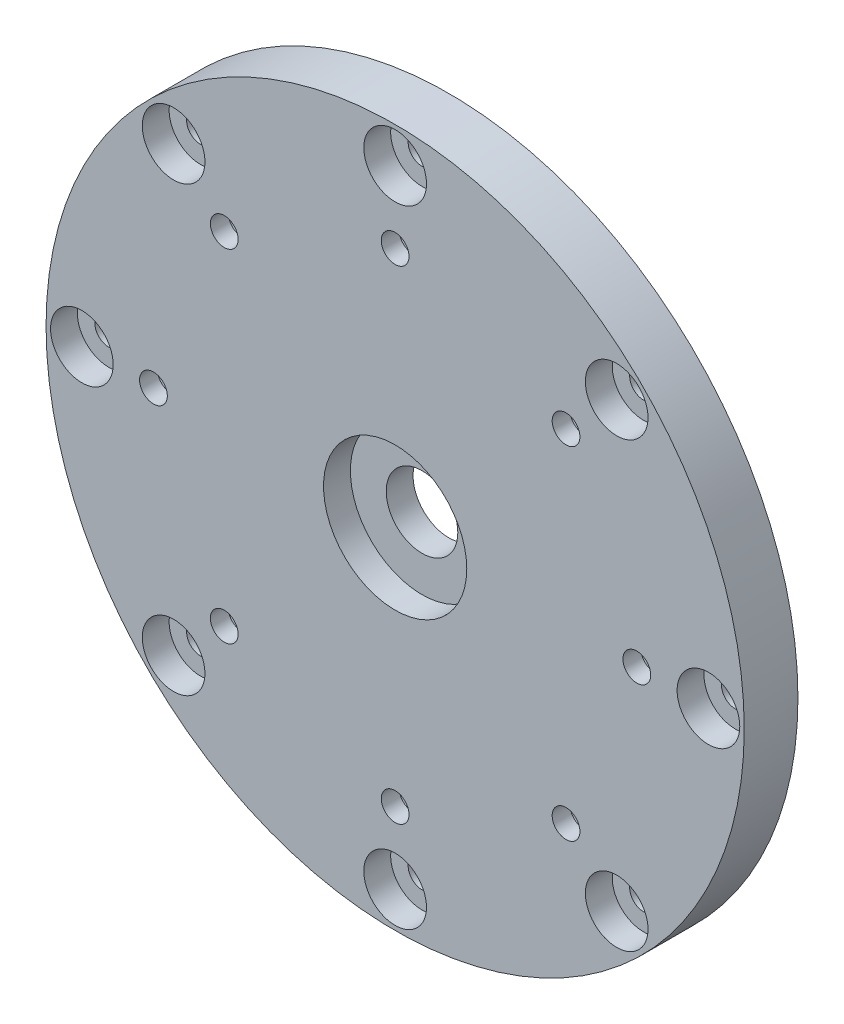
SolidWorks part; units mm, degrees
ref_plane "Front Plane" through (0, 0, 0) normal (0, 0, 1) x (1, 0, 0)
ref_plane "Top Plane" through (0, 0, 0) normal (0, 1, 0) x (1, 0, 0)
ref_plane "Right Plane" through (0, 0, 0) normal (1, 0, 0) x (0, 0, -1)
sketch "Sketch1" plane through (0, 0, 0) normal (0, 0, 1) x (1, 0, 0)
  line L0 (0, 0) -> (-27, 0) construction
  line L1 (0, 0) -> (-35, 0) construction
  circle A1 centre (0, 0) radius 39
  circle A2 centre (-27, 0) radius 1.55
  circle A3 centre (-19.0919, 19.0919) radius 1.55
  circle A4 centre (0, 27) radius 1.55
  circle A5 centre (19.0919, 19.0919) radius 1.55
  circle A6 centre (27, 0) radius 1.55
  circle A7 centre (19.0919, -19.0919) radius 1.55
  circle A8 centre (0, -27) radius 1.55
  circle A9 centre (-19.0919, -19.0919) radius 1.55
  circle A10 centre (0, 0) radius 4
  circle A11 centre (-35, 0) radius 1.55
  circle A12 centre (-24.7487, 24.7487) radius 1.55
  circle A13 centre (0, 35) radius 1.55
  circle A14 centre (24.7487, 24.7487) radius 1.55
  circle A15 centre (35, 0) radius 1.55
  circle A16 centre (24.7487, -24.7487) radius 1.55
  circle A17 centre (0, -35) radius 1.55
  circle A18 centre (-24.7487, -24.7487) radius 1.55
  point P21 (0, 0)
  point P39 (0, 0)
  dimension "D1" = 8
  dimension "D2" = 8
extrude "Boss-Extrude2" add sketch "Sketch1" along normal blind 6
sketch "Sketch2" plane through (0, 0, 6) normal (0, 0, 1) x (1, 0, 0)
  circle A0 centre (0, 0) radius 8
extrude "Cut-Extrude1" cut sketch "Sketch2" against normal blind 3
sketch "Sketch3" plane through (0, 0, 0) normal (0, 0, -1) x (-1, 0, 0)
  circle A0 centre (0, 27) radius 3.5
  circle A1 centre (19.0919, 19.0919) radius 3.5
  circle A2 centre (27, 0) radius 3.5
  circle A3 centre (19.0919, -19.0919) radius 3.5
  circle A4 centre (0, -27) radius 3.5
  circle A5 centre (-19.0919, -19.0919) radius 3.5
  circle A6 centre (-27, 0) radius 3.5
  circle A7 centre (-19.0919, 19.0919) radius 3.5
  point P19 (0, 0)
  point P37 (0, 0)
  dimension "D1" = 8
extrude "Cut-Extrude2" cut sketch "Sketch3" against normal blind 4
sketch "Sketch4" plane through (0, 0, 6) normal (0, 0, 1) x (1, 0, 0)
  circle A0 centre (-35, 0) radius 3.5
  circle A1 centre (-24.7487, 24.7487) radius 3.5
  circle A2 centre (0, 35) radius 3.5
  circle A3 centre (24.7487, 24.7487) radius 3.5
  circle A4 centre (35, 0) radius 3.5
  circle A5 centre (24.7487, -24.7487) radius 3.5
  circle A6 centre (0, -35) radius 3.5
  circle A7 centre (-24.7487, -24.7487) radius 3.5
  point P19 (0, 0)
  dimension "D1" = 8
extrude "Cut-Extrude3" cut sketch "Sketch4" against normal blind 3
